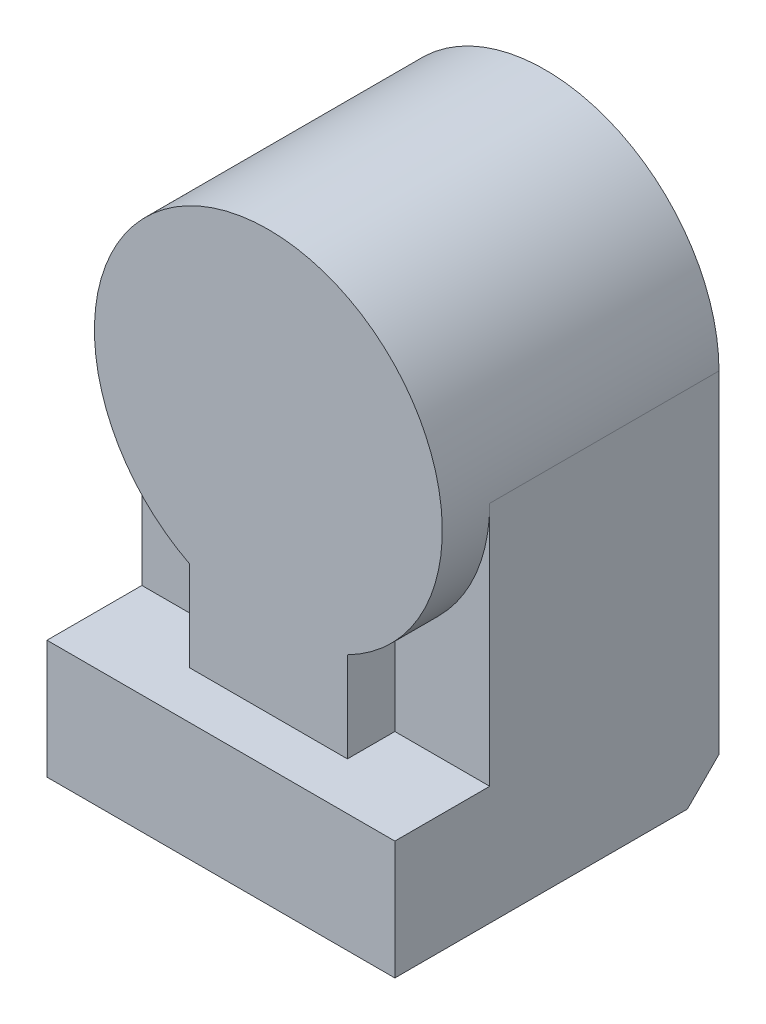
SolidWorks part; units mm, degrees
ref_plane "Plan de face" through (0, 0, 0) normal (0, 0, 1) x (1, 0, 0)
ref_plane "Plan de dessus" through (0, 0, 0) normal (0, 1, 0) x (1, 0, 0)
ref_plane "Plan de droite" through (0, 0, 0) normal (1, 0, 0) x (0, 0, -1)
sketch "Esquisse1" plane through (0, 0, 0) normal (0, 0, 1) x (1, 0, 0)
  line L0 (-11, 0) -> (-11, -23)
  line L1 (-11, -23) -> (11, -23)
  line L2 (11, 0) -> (11, -23)
  arc A0 (11, 0) -> (-11, 0) centre (0, 0) ccw
  dimension "D1" = 22
  dimension "D2" = 23
extrude "Boss.-Extru.1" add sketch "Esquisse1" along normal blind 14.5
chamfer "Chanfrein1" distance 2 distance2 2 1 edges at (0, -23, 0)
sketch "Esquisse2" plane through (0, 0, 14.5) normal (0, 0, 1) x (1, 0, 0)
  line L0 (11, -23) -> (11, 0) construction
  line L1 (-11, -23) -> (11, -23)
  line L2 (-11, -23) -> (-11, -15.5)
  line L3 (-11, -15.5) -> (11, -15.5)
  line L4 (11, -23) -> (11, -15.5)
  dimension "D1" = 7.5
extrude "Boss.-Extru.2" add sketch "Esquisse2" along normal blind 6
sketch "Esquisse3" plane through (0, 0, 14.5) normal (0, 0, 1) x (1, 0, 0)
  line L0 (-5, -9.798) -> (-5, -15.5)
  line L1 (11, -15.5) -> (-11, -15.5) construction
  line L2 (-5, -15.5) -> (5, -15.5)
  line L3 (11, -15.5) -> (-11, -15.5) construction
  line L4 (5, -15.5) -> (5, -9.798)
  arc A0 (5, -9.798) -> (-5, -9.798) centre (0, 0) ccw
  dimension "D3" = 22
  dimension "D1" = 10
  dimension "D2" = 5
extrude "Boss.-Extru.3" add sketch "Esquisse3" along normal blind 3
